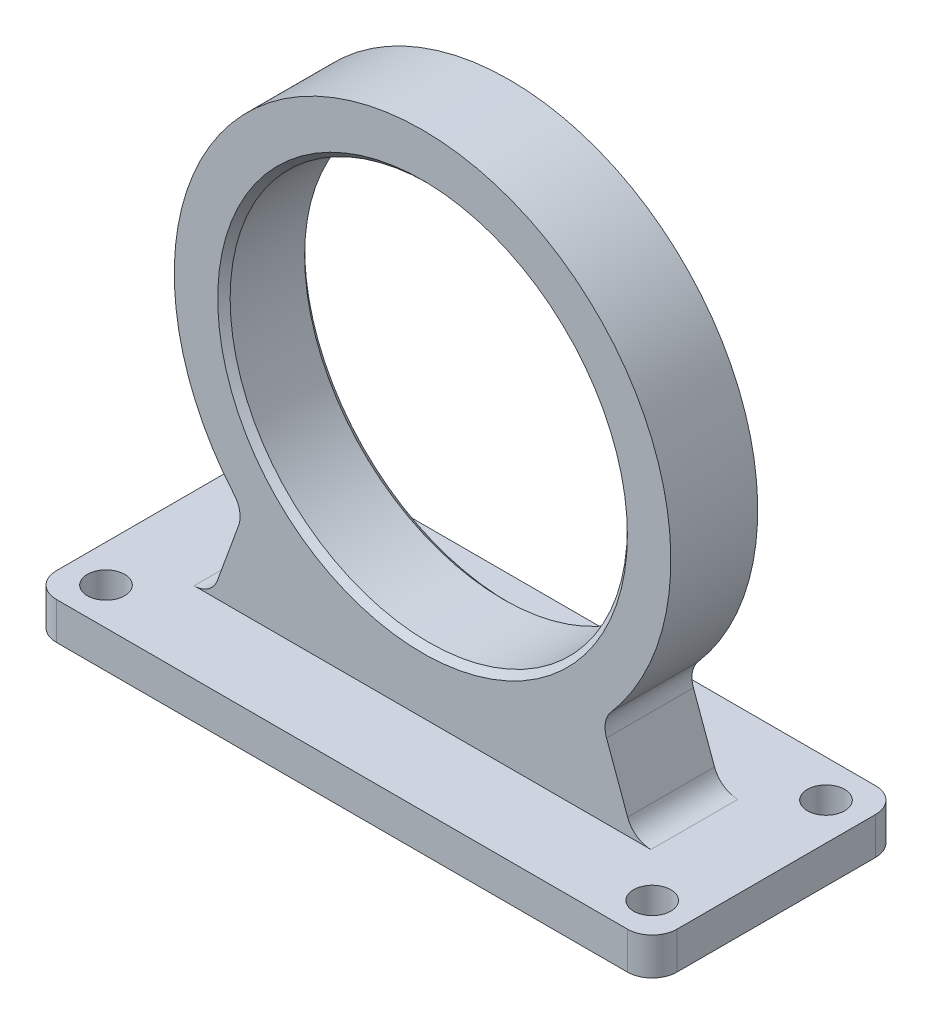
SolidWorks part; units mm, degrees
material "6061-T6 (SS)"
ref_plane "前视基准面" through (0, 0, 0) normal (0, 0, 1) x (1, 0, 0)
ref_plane "上视基准面" through (0, 0, 0) normal (0, 1, 0) x (1, 0, 0)
ref_plane "右视基准面" through (0, 0, 0) normal (1, 0, 0) x (0, 0, -1)
sketch "草图1" plane through (0, 0, 0) normal (0, 0, 1) x (1, 0, 0)
  line L0 (-83.6584, 0) -> (96.4234, 0) construction
  line L1 (0, 91.9147) -> (0, -59.4902) construction
  line L2 (-14.4061, 10.1268) -> (-17, 3)
  line L3 (-25, 3) -> (25, 3)
  line L4 (-25, 3) -> (-25, 0)
  line L5 (-25, 0) -> (25, 0)
  line L6 (25, 3) -> (25, 0)
  line L7 (-25, 3) -> (25, 0) construction
  line L8 (-25, 0) -> (25, 3) construction
  line L9 (14.4061, 10.1268) -> (17, 3)
  circle A0 centre (0, 24) radius 16
  circle A1 centre (0, 24) radius 20
  point P9 (0, 1.5)
  dimension "D1" = 32
  dimension "D3" = 3
  dimension "D4" = 24
  dimension "D5" = 50
  dimension "D6" = 8
  dimension "D7" = 70
  dimension "D2" = 4
extrude "凸台-拉伸1" add sketch "草图1" along normal mid plane 7 contours A1 L3 A0 | A1 L3 L9 | A1 L2 L3 | A1 L3 L4 L5 L6 | L3 A1
sketch "草图2" plane through (0, 0, 0) normal (0, -1, 0) x (1, 0, 0)
  line L5 (-25, 10) -> (25, 10)
  line L7 (-47.5443, 0) -> (49.0493, 0) construction
  line L8 (0, -39.4744) -> (0, 27.4744) construction
  line L12 (-25, 10) -> (-25, -10)
  line L13 (-25, -10) -> (25, -10)
  line L14 (25, 10) -> (25, -10)
  line L15 (-25, 10) -> (25, -10) construction
  line L16 (-25, -10) -> (25, 10) construction
  circle A8 centre (-22, -7) radius 1.5
  circle A9 centre (22, -7) radius 1.5
  circle A10 centre (22, 7) radius 1.5
  circle A11 centre (-22, 7) radius 1.5
  point P0 (0, 0)
  dimension "D2" = 50
  dimension "D4" = 3
  dimension "D3" = 3
  dimension "D1" = 20
  dimension "D5" = 3
extrude "凸台-拉伸2" add sketch "草图2" against normal up to surface (3 mm away) up to face at (-21, 3, 0)
fillet "圆角1" radius 2 4 edges at (-17, 3, 0) (-14.4061, 10.1268, 0) (17, 3, 0) (14.4061, 10.1268, 0)
fillet "圆角2" radius 2 4 edges at (25, 1.5, 10) (-25, 1.5, 10) (25, 1.5, -10) (-25, 1.5, -10)
chamfer "倒角1" distance 0.5 angle 45 2 edges at (16, 24, 3.5) (16, 24, -3.5)
move or copy body "实体-移动/复制1" [suppressed] bodies to move or copy 107
